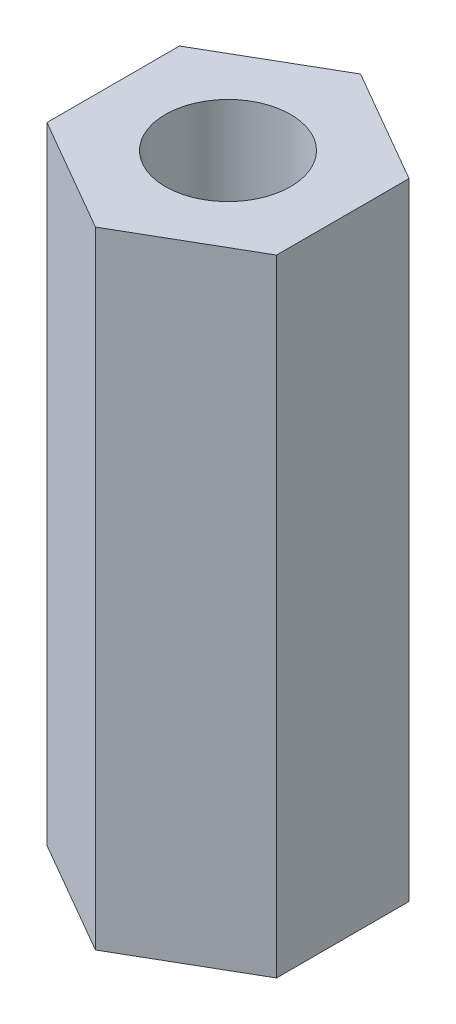
SolidWorks part; units mm, degrees
ref_plane "Plan de face" through (0, 0, 0) normal (0, 0, 1) x (1, 0, 0)
ref_plane "Plan de dessus" through (0, 0, 0) normal (0, 1, 0) x (1, 0, 0)
ref_plane "Plan de droite" through (0, 0, 0) normal (1, 0, 0) x (0, 0, -1)
sketch "Sketch1" plane through (0, 0, 0) normal (0, 1, 0) x (1, 0, 0)
  line L1 (0, -3.1754) -> (2.75, -1.5877)
  line L2 (2.75, -1.5877) -> (2.75, 1.5877)
  line L3 (2.75, 1.5877) -> (0, 3.1754)
  line L4 (0, 3.1754) -> (-2.75, 1.5877)
  line L5 (-2.75, 1.5877) -> (-2.75, -1.5877)
  line L6 (-2.75, -1.5877) -> (0, -3.1754)
  circle A0 centre (0, 0) radius 1.5
  circle A1 centre (0, 0) radius 2.75 construction
  dimension "D1" = 5.5
extrude "Boss-Extrude1" add sketch "Sketch1" along normal mid plane 15
